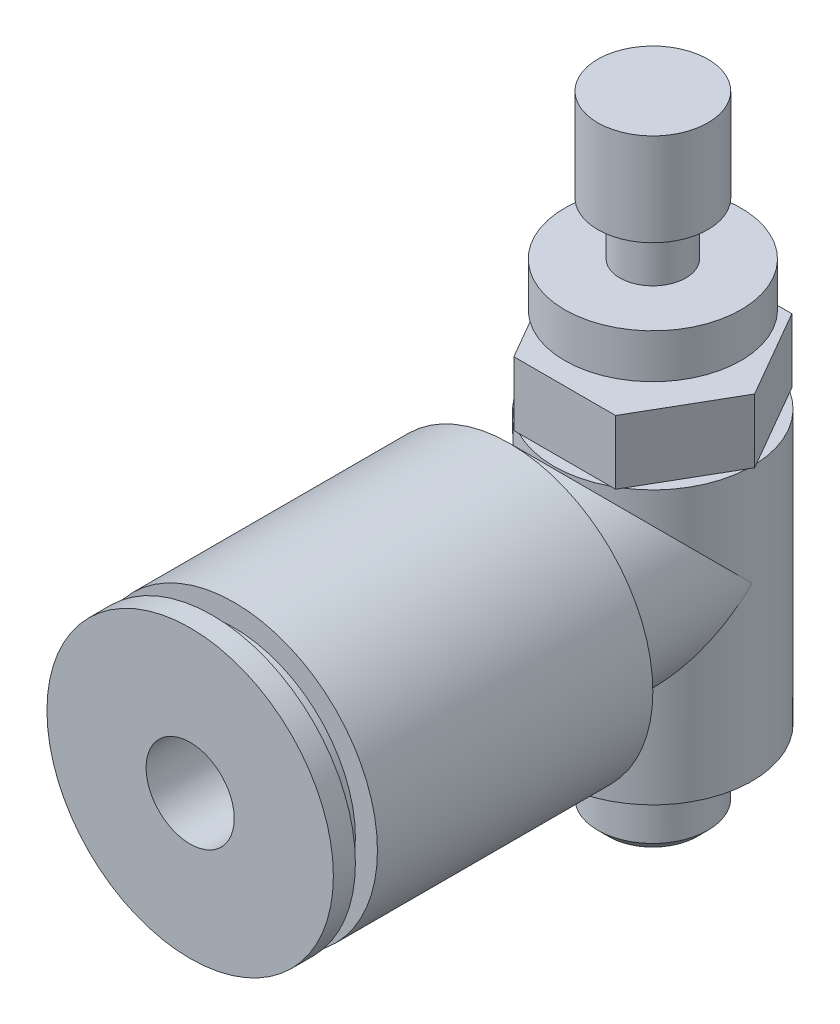
SolidWorks part; units mm, degrees
ref_plane "前视基准面" through (0, 0, 0) normal (0, 0, 1) x (1, 0, 0)
ref_plane "上视基准面" through (0, 0, 0) normal (0, 1, 0) x (1, 0, 0)
ref_plane "右视基准面" through (0, 0, 0) normal (1, 0, 0) x (0, 0, -1)
ref_plane "基准面4" through (0, 7.5, 0) normal (0, 1, 0) x (-1, 0, 0)
sketch "草图1" plane through (0, 7.5, 0) normal (0, 1, 0) x (-1, 0, 0)
  line L0 (2.3094, 4) -> (-2.3094, 4)
  line L1 (-2.3094, 4) -> (-4.6188, 0)
  line L2 (-4.6188, 0) -> (-2.3094, -4)
  line L3 (-2.3094, -4) -> (2.3094, -4)
  line L4 (2.3094, -4) -> (4.6188, 0)
  line L5 (4.6188, 0) -> (2.3094, 4)
extrude "凸台-拉伸1" add sketch "草图1" against normal blind 2.9
ref_plane "基准面5" through (0, 0, 0) normal (0, 0, -1) x (-1, 0, 0)
sketch "草图2" plane through (0, 0, 0) normal (0, 0, -1) x (-1, 0, 0)
  line L0 (-2.5, -11.2) -> (0, -11.2)
  line L1 (0, -11.2) -> (0, 4.6)
  line L2 (0, 4.6) -> (-4.5, 4.6)
  line L3 (-4.5, 4.6) -> (-4.5, -7.78)
  line L4 (-4.5, -7.78) -> (-2.5, -7.78)
  line L5 (-2.5, -7.78) -> (-2.5, -11.2)
  line L6 (0, -11.2) -> (0, 4.6) construction
revolve "旋转1" add sketch "草图2" angle 360 about L6
sketch "草图3" plane through (0, 0, 0) normal (0, 1, 0) x (1, 0, 0)
  line L0 (0, -21) -> (6.5, -21)
  line L1 (6.5, -21) -> (6.5, -20)
  line L2 (6.5, -20) -> (5.5, -20)
  line L3 (5.5, -20) -> (5.5, -19)
  line L4 (5.5, -19) -> (6.5, -19)
  line L5 (6.5, -19) -> (6.5, -6.5)
  line L6 (6.5, -6.5) -> (4.5, -6.5)
  line L7 (4.5, -6.5) -> (4.5, 0)
  line L8 (4.5, 0) -> (0, 0)
  line L9 (0, 0) -> (0, -21)
  line L10 (0, 0) -> (0, -21) construction
revolve "旋转2" add sketch "草图3" angle 360 about L10
sketch "草图4" plane through (0, 0, 0) normal (0, 0, -1) x (-1, 0, 0)
  line L0 (-2.5, 7.5) -> (0, 7.5)
  line L1 (0, 7.5) -> (0, 17.1)
  line L2 (0, 17.1) -> (-2.5, 17.1)
  line L3 (-2.5, 17.1) -> (-2.5, 12.9)
  line L4 (-2.5, 12.9) -> (-1.5, 12.9)
  line L5 (-1.5, 12.9) -> (-1.5, 10.5)
  line L6 (-1.5, 10.5) -> (-4, 10.5)
  line L7 (-4, 10.5) -> (-4, 8.5)
  line L8 (-4, 8.5) -> (-2.5, 8.5)
  line L9 (-2.5, 8.5) -> (-2.5, 7.5)
  line L10 (0, 7.5) -> (0, 17.1) construction
revolve "旋转3" add sketch "草图4" angle 360 about L10
hole_wizard "孔1" positions "草图6" profile "草图5" legacy
sketch "草图6" plane through (0, 0, 21) normal (0, 0, 1) x (1, 0, 0)
  point P0 (0, 0)
sketch "草图5" plane through (0, 0, 21) normal (1, 0, 0) x (0, -1, 0)
  line L0 (0, 0) -> (0, 16)
  line L1 (0, 16) -> (2, 16)
  line L2 (2, 16) -> (2, 0)
  line L3 (2, 0) -> (0, 0)
  line L4 (0, 110) -> (0, -10) construction
  dimension "直径" = 4
  dimension "深度" = 16
chamfer "倒角1" distance 0.49 angle 45 1 edges at (0, -11.2, 2.5)
